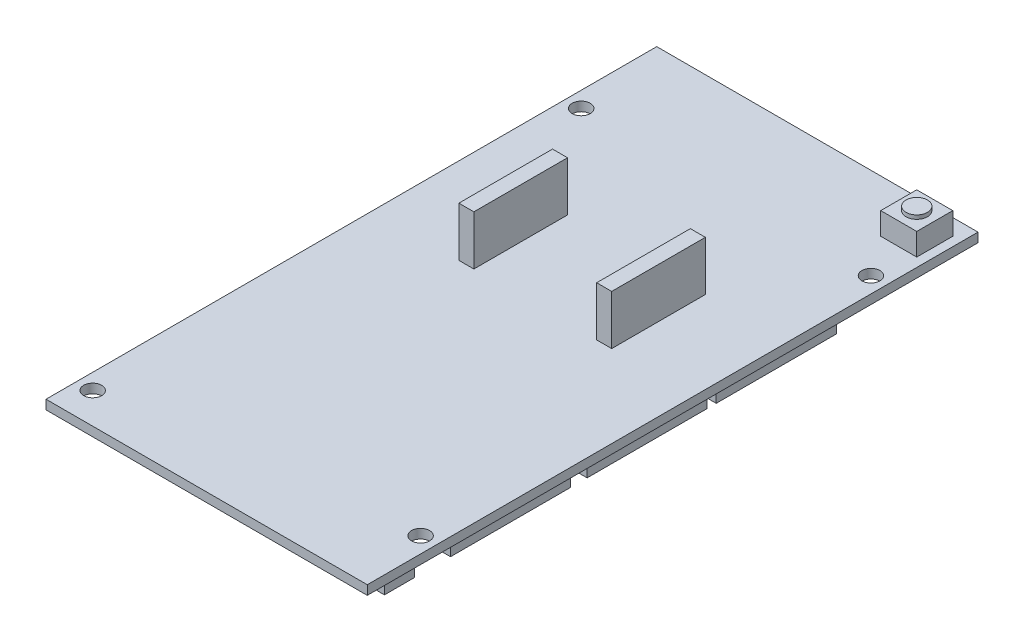
SolidWorks part; units mm, degrees
ref_plane "Front Plane" through (0, 0, 0) normal (0, 0, 1) x (1, 0, 0)
ref_plane "Top Plane" through (0, 0, 0) normal (0, 1, 0) x (1, 0, 0)
ref_plane "Right Plane" through (0, 0, 0) normal (1, 0, 0) x (0, 0, -1)
sketch "Sketch1" plane through (0, 0, 0) normal (0, 1, 0) x (1, 0, 0)
  line L4 (26.75, 50.85) -> (-26.75, 50.85)
  line L5 (26.75, -50.85) -> (26.75, 50.85)
  line L6 (-26.75, -50.85) -> (26.75, -50.85)
  line L7 (-26.75, 50.85) -> (-26.75, -50.85)
  line L8 (26.75, 50.85) -> (-26.75, 50.85)
  line L9 (26.75, -50.85) -> (26.75, 50.85)
  line L10 (-26.75, -50.85) -> (26.75, -50.85)
  line L11 (-26.75, 50.85) -> (-26.75, -50.85)
  circle A1 centre (24.125, -39.35) radius 1.5
  circle A2 centre (24.125, -39.35) radius 1.5
  circle A3 centre (-24.125, -45.7) radius 1.5
  circle A4 centre (-24.125, -45.7) radius 1.5
  circle A5 centre (24.125, 35.65) radius 1.5
  circle A6 centre (24.125, 35.65) radius 1.5
  circle A7 centre (-24.125, 35.65) radius 1.5
  circle A8 centre (-24.125, 35.65) radius 1.5
  dimension "D1" = 0
  dimension "D2" = 0
  dimension "D3" = 0
  dimension "D4" = 0
  dimension "D5" = 0
extrude "Boss-Extrude1" add sketch "Sketch1" along normal blind 1.54
sketch "Sketch2" plane through (0, 1.54, 0) normal (0, 1, 0) x (1, 0, 0)
  line L0 (26.75, -50.85) -> (26.75, 50.85) construction
  line L1 (10.55, 19.15) -> (13.05, 19.15)
  line L2 (10.55, 19.15) -> (10.55, 3.55)
  line L3 (10.55, 3.55) -> (13.05, 3.55)
  line L4 (13.05, 19.15) -> (13.05, 3.55)
  line L5 (-12.4, 19.15) -> (-9.9, 19.15)
  line L6 (-12.4, 19.15) -> (-12.4, 3.55)
  line L7 (-12.4, 3.55) -> (-9.9, 3.55)
  line L8 (-9.9, 19.15) -> (-9.9, 3.55)
  line L9 (-26.75, 50.85) -> (-26.75, -50.85) construction
  line L10 (26.75, 50.85) -> (-26.75, 50.85) construction
  point P8 (-9.9, 11.35)
  point P9 (10.55, 11.35)
  dimension "D1" = 13.7
  dimension "D2" = 2.5
  dimension "D3" = 15.6
  dimension "D4" = 14.35
  dimension "D5" = 31.7
extrude "Boss-Extrude2" add sketch "Sketch2" along normal blind 8.25
sketch "Sketch3" plane through (0, 1.54, 0) normal (0, 1, 0) x (1, 0, 0)
  line L0 (26.75, -50.85) -> (26.75, 50.85) construction
  line L5 (19.25, 48.15) -> (25.25, 48.15)
  line L6 (19.25, 48.15) -> (19.25, 42.15)
  line L7 (19.25, 42.15) -> (25.25, 42.15)
  line L8 (25.25, 48.15) -> (25.25, 42.15)
  line L9 (19.25, 48.15) -> (25.25, 42.15) construction
  line L10 (19.25, 42.15) -> (25.25, 48.15) construction
  line L11 (26.75, 50.85) -> (-26.75, 50.85) construction
  point P0 (22.25, 45.15)
  dimension "D1" = 6
  dimension "D2" = 1.5
  dimension "D3" = 2.7
extrude "Boss-Extrude3" add sketch "Sketch3" along normal blind 3.7
sketch "Sketch5" plane through (0, 5.24, 0) normal (0, 1, 0) x (1, 0, 0)
  circle A0 centre (22.25, 45.15) radius 1.785
  dimension "D1" = 3.57
extrude "Boss-Extrude5" add sketch "Sketch5" along normal blind 0.64
sketch "Sketch4" plane through (0, 0, 0) normal (0, -1, 0) x (1, 0, 0)
  line L0 (-23.9, 21.95) -> (-23.9, 19.2) construction
  line L1 (-19.89, 46.85) -> (25.61, 46.85)
  line L2 (-19.89, 46.85) -> (-19.89, 41.85)
  line L3 (-19.89, 41.85) -> (25.61, 41.85)
  line L4 (25.61, 46.85) -> (25.61, 41.85)
  line L5 (23.11, 35.85) -> (25.61, 35.85)
  line L6 (23.11, 35.85) -> (23.11, 15.85)
  line L7 (23.11, 15.85) -> (25.61, 15.85)
  line L8 (25.61, 35.85) -> (25.61, 15.85)
  line L9 (20.61, 13.1) -> (25.61, 13.1)
  line L10 (20.61, 13.1) -> (20.61, -6.9)
  line L11 (20.61, -6.9) -> (25.61, -6.9)
  line L12 (25.61, 13.1) -> (25.61, -6.9)
  line L13 (20.61, -8.4) -> (25.61, -8.4)
  line L14 (20.61, -8.4) -> (20.61, -28.4)
  line L15 (20.61, -28.4) -> (25.61, -28.4)
  line L16 (25.61, -8.4) -> (25.61, -28.4)
  line L17 (-25.15, 41.95) -> (-22.65, 41.95)
  line L18 (-25.15, 41.95) -> (-25.15, 21.95)
  line L19 (-25.15, 21.95) -> (-22.65, 21.95)
  line L20 (-22.65, 41.95) -> (-22.65, 21.95)
  line L21 (-25.15, 19.2) -> (-22.65, 19.2)
  line L22 (-25.15, 19.2) -> (-25.15, -0.8)
  line L23 (-25.15, -0.8) -> (-22.65, -0.8)
  line L24 (-22.65, 19.2) -> (-22.65, -0.8)
  line L25 (-25.15, -3.55) -> (-22.65, -3.55)
  line L26 (-25.15, -3.55) -> (-25.15, -18.45)
  line L27 (-25.15, -18.45) -> (-22.65, -18.45)
  line L28 (-22.65, -3.55) -> (-22.65, -18.45)
  line L29 (-23.9, -0.8) -> (-23.9, -3.55) construction
  line L30 (24.36, 15.85) -> (24.36, 13.1) construction
  line L31 (-26.75, 50.85) -> (26.75, 50.85) construction
  line L32 (26.75, 50.85) -> (26.75, -50.85) construction
  line L33 (-26.75, -50.85) -> (-26.75, 50.85) construction
  dimension "D1" = 20
  dimension "D2" = 8.9
  dimension "D3" = 2.5
  dimension "D4" = 5
  dimension "D5" = 14.9
  dimension "D6" = 2.75
  dimension "D7" = 45.5
  dimension "D8" = 1.14
  dimension "D9" = 6
  dimension "D10" = 4
  dimension "D11" = 1.5
  dimension "D12" = 1.6
extrude "Boss-Extrude4" add sketch "Sketch4" along normal blind 2.5
